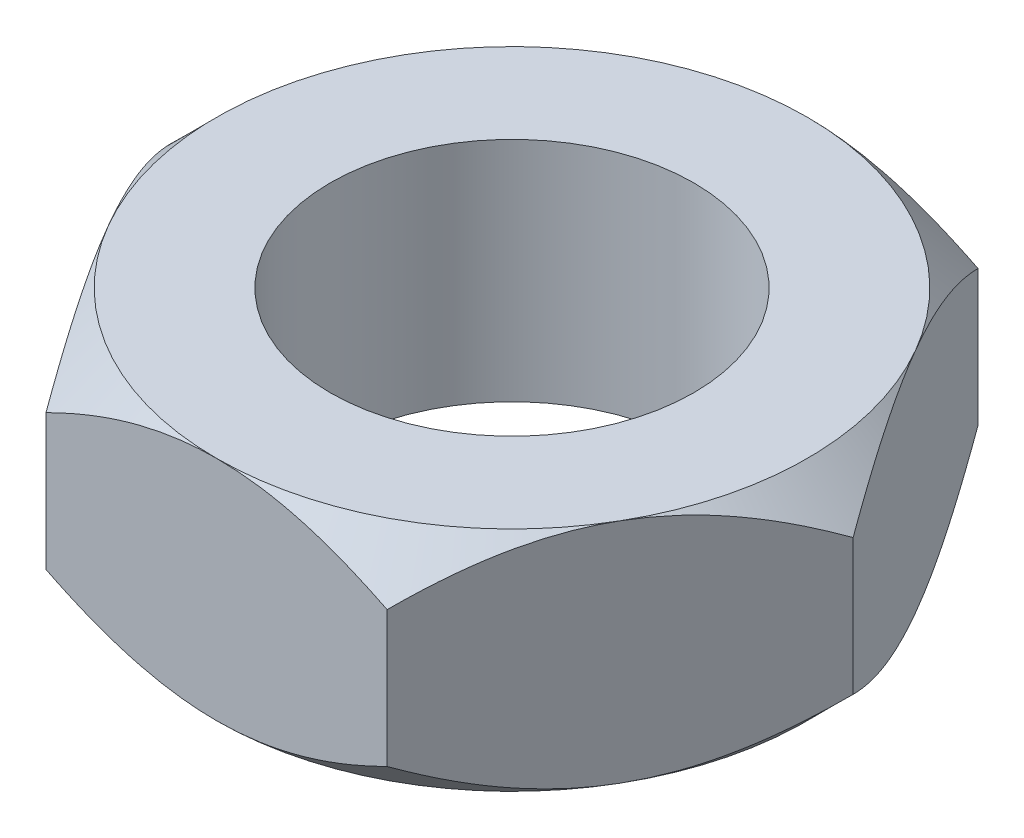
SolidWorks part; units mm, degrees
ref_plane "Front Plane" through (0, 0, 0) normal (0, 0, 1) x (1, 0, 0)
ref_plane "Top Plane" through (0, 0, 0) normal (0, 1, 0) x (1, 0, 0)
ref_plane "Right Plane" through (0, 0, 0) normal (1, 0, 0) x (0, 0, -1)
sketch "Sketch1" plane through (0, 0, 0) normal (0, 1, 0) x (1, 0, 0)
  line L1 (7.5056, 0) -> (3.7528, 6.5)
  line L2 (3.7528, 6.5) -> (-3.7528, 6.5)
  line L3 (-3.7528, 6.5) -> (-7.5056, 0)
  line L4 (-7.5056, 0) -> (-3.7528, -6.5)
  line L5 (-3.7528, -6.5) -> (3.7528, -6.5)
  line L6 (3.7528, -6.5) -> (7.5056, 0)
  circle A0 centre (0, 0) radius 6.5 construction
  dimension "D1" = 13
extrude "Boss-Extrude1" add sketch "Sketch1" along normal blind 5
sketch "Sketch2" plane through (0, 5, 0) normal (0, 1, 0) x (1, 0, 0)
  circle A0 centre (0, 0) radius 6.5
extrude "Cut-Extrude1" cut sketch "Sketch2" against normal through all draft 45 flip side to cut
ref_plane "Plane1" through (0, 2.5, 0) normal (0, 1, 0) x (1, 0, 0)
mirror "Mirror1" about plane through (0, 2.5, 0) normal (0, 1, 0) of "Cut-Extrude1"
sketch "Sketch3" plane through (0, 5, 0) normal (0, 1, 0) x (1, 0, 0)
  circle A0 centre (0, 0) radius 4
  dimension "D1" = 8
extrude "Cut-Extrude2" cut sketch "Sketch3" against normal through all
